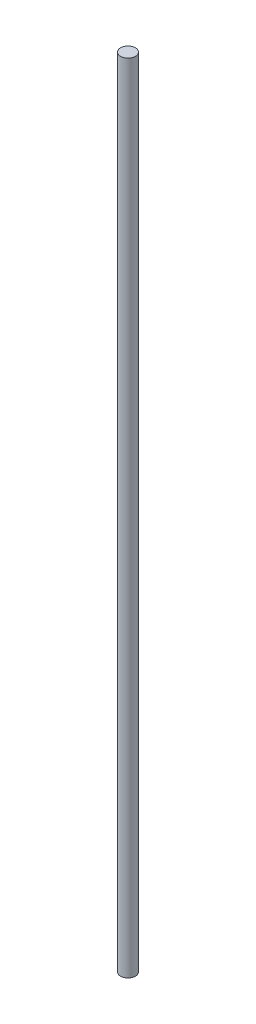
SolidWorks part; units mm, degrees
material "AISI 1020"
ref_plane "Front Plane" through (0, 0, 0) normal (0, 0, 1) x (1, 0, 0)
ref_plane "Top Plane" through (0, 0, 0) normal (0, 1, 0) x (1, 0, 0)
ref_plane "Right Plane" through (0, 0, 0) normal (1, 0, 0) x (0, 0, -1)
sketch "Sketch1" plane through (0, 0, 0) normal (0, 1, 0) x (1, 0, 0)
  circle A0 centre (0, 0) radius 4
  dimension "D1" = 8
extrude "Boss-Extrude1" add sketch "Sketch1" along normal mid plane 430
cosmetic thread "Cosmetic Thread1" parameters "D2"=7
